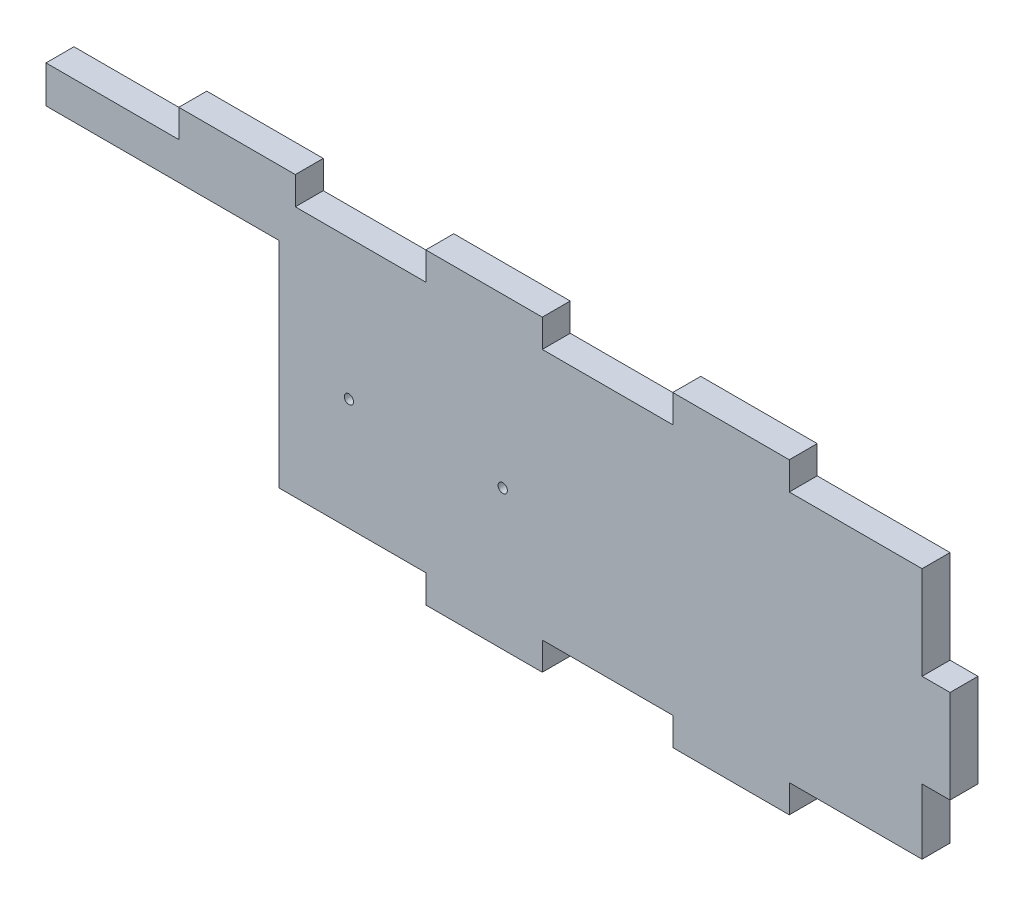
SolidWorks part; units mm, degrees
ref_plane "Plan de face" through (0, 0, 0) normal (0, 0, 1) x (1, 0, 0)
ref_plane "Plan de dessus" through (0, 0, 0) normal (0, 1, 0) x (1, 0, 0)
ref_plane "Plan de droite" through (0, 0, 0) normal (1, 0, 0) x (0, 0, -1)
sketch "Esquisse1" plane through (0, 0, 0) normal (0, 0, 1) x (1, 0, 0)
  line L1 (94, -30) -> (-94, -30)
  line L2 (94, -30) -> (94, 30)
  line L3 (94, 30) -> (-94, 30)
  line L4 (-94, -30) -> (-94, 30)
  line L5 (94, -30) -> (-94, 30) construction
  line L6 (94, 30) -> (-94, -30) construction
  point P0 (0, 0)
extrude "Boss.-Extru.1" add sketch "Esquisse1" along normal blind 6
sketch "Esquisse3" plane through (0, 0, 0) normal (0, 0, -1) x (-1, 0, 0)
  line L1 (94, -30) -> (44, -30)
  line L2 (94, -30) -> (94, 22)
  line L3 (94, 22) -> (44, 22)
  line L4 (44, -30) -> (44, 22)
extrude "Enlèv. mat.-Extru.2" cut sketch "Esquisse3" against normal blind 10
sketch "Esquisse6" plane through (94, 0, 0) normal (1, 0, 0) x (0, 0, -1)
  line L0 (-6, -30) -> (-6, 30) construction
  line L1 (-6, 10) -> (0, 10)
  line L2 (-6, 10) -> (-6, -10)
  line L3 (-6, -10) -> (0, -10)
  line L4 (0, 10) -> (0, -10)
  line L5 (0, -30) -> (0, 30) construction
  line L6 (-6, 30) -> (0, 30) construction
  point P8 (-3, 30)
  dimension "D1" = 20
  dimension "D2" = 20
extrude "Boss.-Extru.2" add sketch "Esquisse6" along normal blind 6
sketch "Esquisse7" plane through (0, 30, 0) normal (0, 1, 0) x (1, 0, 0)
  line L0 (94, 0) -> (-94, 0) construction
  line L1 (94, -6) -> (-94, -6) construction
  line L2 (65.5, 0) -> (40.5, 0)
  line L3 (65.5, 0) -> (65.5, -6)
  line L4 (65.5, -6) -> (40.5, -6)
  line L5 (40.5, 0) -> (40.5, -6)
  line L6 (94, -6) -> (94, 0) construction
  line L7 (12.5, 0) -> (-12.5, 0)
  line L8 (12.5, 0) -> (12.5, -6)
  line L9 (12.5, -6) -> (-12.5, -6)
  line L10 (-12.5, 0) -> (-12.5, -6)
  line L11 (-40.5, 0) -> (-65.5, 0)
  line L12 (-40.5, 0) -> (-40.5, -6)
  line L13 (-40.5, -6) -> (-65.5, -6)
  line L14 (-65.5, 0) -> (-65.5, -6)
  point P16 (94, -3)
  dimension "D1" = 25
  dimension "D2" = 25
  dimension "D3" = 25
  dimension "D4" = 28
  dimension "D5" = 28
  dimension "D6" = 28.5
extrude "Boss.-Extru.3" add sketch "Esquisse7" along normal blind 6
sketch "Esquisse8" plane through (0, 0, 0) normal (0, 0, -1) x (-1, 0, 0)
  line L0 (44, 22) -> (44, -30) construction
  line L1 (12.5, 30) -> (40.5, 30) construction
  circle A0 centre (29, 0) radius 1
  circle A1 centre (-4, 0) radius 1
  point P2 (44, -4)
  dimension "D1" = 15
  dimension "D3" = 48
  dimension "D2" = 30
extrude "Enlèv. mat.-Extru.4" cut sketch "Esquisse8" against normal blind 10
sketch "Esquisse9" plane through (0, 0, 0) normal (0, 0, -1) x (-1, 0, 0)
  line L0 (44, -30) -> (-94, -30) construction
  line L1 (-94, -30) -> (-65.5, -30)
  line L2 (-94, -30) -> (-94, -24)
  line L3 (-94, -24) -> (-65.5, -24)
  line L4 (-65.5, -30) -> (-65.5, -24)
  line L5 (-40.5, -30) -> (-12.5, -30)
  line L6 (-40.5, -30) -> (-40.5, -24)
  line L7 (-40.5, -24) -> (-12.5, -24)
  line L8 (-12.5, -30) -> (-12.5, -24)
  line L9 (44, 22) -> (44, -30) construction
  line L10 (12.5, -30) -> (44, -30)
  line L11 (12.5, -30) -> (12.5, -24)
  line L12 (12.5, -24) -> (44, -24)
  line L13 (44, -30) -> (44, -24)
  dimension "D1" = 6
  dimension "D2" = 6
  dimension "D3" = 6
  dimension "D4" = 0
  dimension "D5" = 0
  dimension "D6" = 0
  dimension "D7" = 0
  dimension "D8" = 0
extrude "Enlèv. mat.-Extru.5" cut sketch "Esquisse9" against normal blind 10
